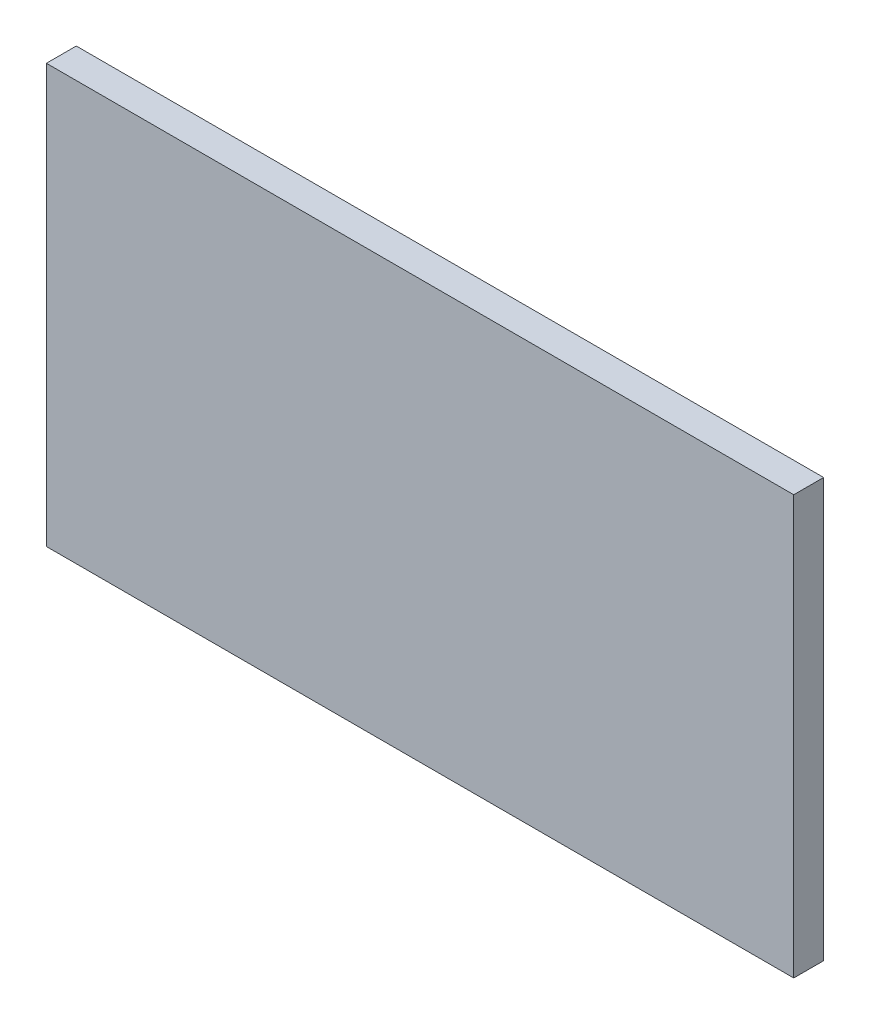
SolidWorks part; units mm, degrees
ref_plane "Front Plane" through (0, 0, 0) normal (0, 0, 1) x (1, 0, 0)
ref_plane "Top Plane" through (0, 0, 0) normal (0, 1, 0) x (1, 0, 0)
ref_plane "Right Plane" through (0, 0, 0) normal (1, 0, 0) x (0, 0, -1)
sketch "Sketch1" plane through (0, 0, 0) normal (0, 0, 1) x (1, 0, 0)
  line L1 (158.75, -88.9) -> (-158.75, -88.9)
  line L2 (158.75, -88.9) -> (158.75, 88.9)
  line L3 (158.75, 88.9) -> (-158.75, 88.9)
  line L4 (-158.75, -88.9) -> (-158.75, 88.9)
  line L5 (158.75, -88.9) -> (-158.75, 88.9) construction
  line L6 (158.75, 88.9) -> (-158.75, -88.9) construction
  point P0 (0, 0)
  dimension "D1" = 177.8
  dimension "D2" = 317.5
extrude "Boss-Extrude1" add sketch "Sketch1" along normal blind 12.7
